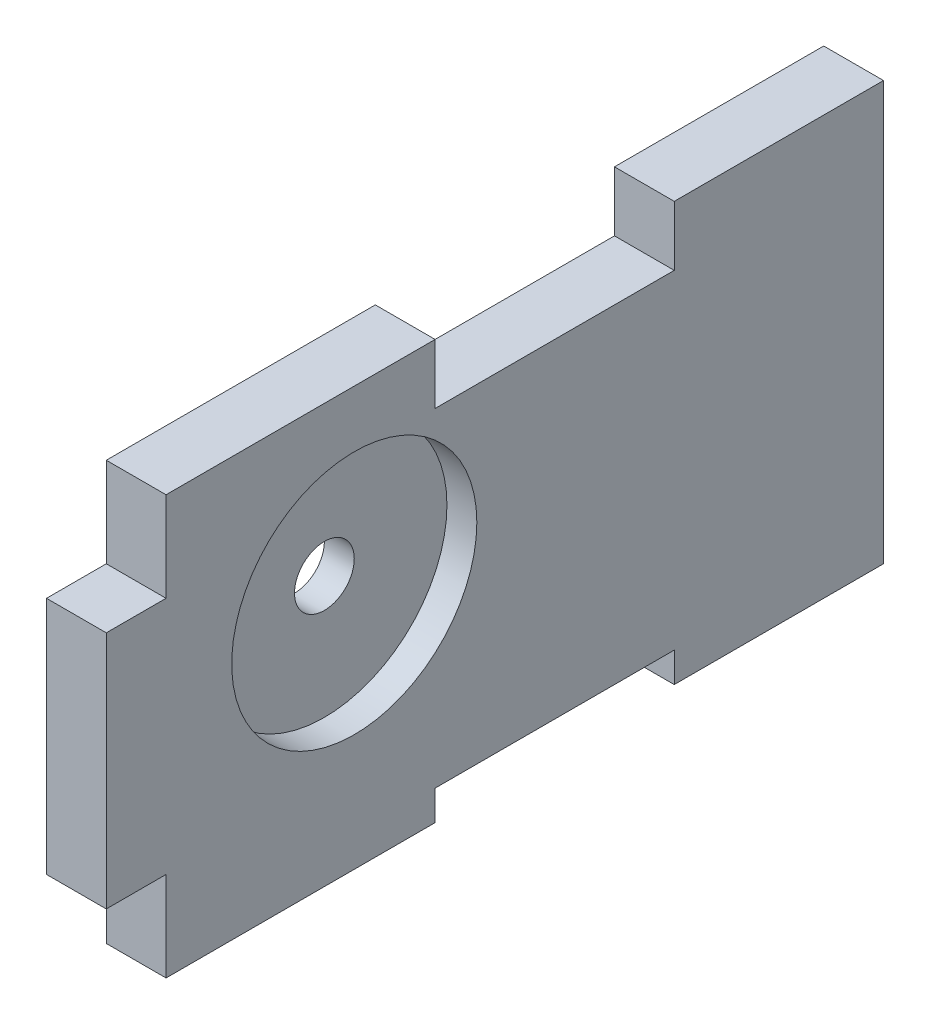
SolidWorks part; units mm, degrees
ref_plane "Front Plane" through (0, 0, 0) normal (0, 0, 1) x (1, 0, 0)
ref_plane "Top Plane" through (0, 0, 0) normal (0, 1, 0) x (1, 0, 0)
ref_plane "Right Plane" through (0, 0, 0) normal (1, 0, 0) x (0, 0, -1)
sketch "Sketch1" plane through (0, 0, 0) normal (1, 0, 0) x (0, 0, -1)
  line L1 (-130, 70) -> (0, 70)
  line L2 (-130, 70) -> (-130, 0)
  line L3 (-130, 0) -> (0, 0)
  line L4 (0, 70) -> (0, 0)
  line L5 (-130, 70) -> (-120, 70)
  line L6 (-130, 70) -> (-130, 55)
  line L7 (-130, 55) -> (-120, 55)
  line L8 (-120, 70) -> (-120, 55)
  line L9 (-130, 0) -> (-120, 0)
  line L10 (-130, 0) -> (-130, 15)
  line L11 (-130, 15) -> (-120, 15)
  line L12 (-120, 0) -> (-120, 15)
  line L13 (0, 70) -> (-10, 70)
  line L14 (0, 70) -> (0, 55)
  line L17 (0, 0) -> (-10, 0)
  line L18 (0, 0) -> (0, 15)
  line L21 (-75, 70) -> (-35, 70)
  line L22 (-75, 70) -> (-75, 60)
  line L23 (-75, 60) -> (-35, 60)
  line L24 (-35, 70) -> (-35, 60)
  line L25 (-75, 0) -> (-35, 0)
  line L26 (-75, 0) -> (-75, 5)
  line L27 (-75, 5) -> (-35, 5)
  line L28 (-35, 0) -> (-35, 5)
  dimension "D1" = 130
  dimension "D2" = 70
  dimension "D3" = 10
  dimension "D4" = 15
  dimension "D5" = 10
  dimension "D6" = 15
  dimension "D11" = 10
  dimension "D12" = 40
  dimension "D13" = 55
  dimension "D14" = 55
  dimension "D15" = 40
  dimension "D16" = 5
extrude "Boss-Extrude1" add sketch "Sketch1" along normal blind 10
sketch "Sketch2" plane through (10, 0, 0) normal (1, 0, 0) x (0, 0, -1)
  line L1 (-130, 55) -> (-130, 15) construction
  line L2 (-75, 5) -> (-35, 5) construction
  circle A0 centre (-88.52, 40) radius 20.5
  dimension "D3" = 41
  dimension "D1" = 35
  dimension "D2" = 41.48
extrude "Cut-Extrude1" cut sketch "Sketch2" against normal blind 5 contours A0
sketch "Sketch4" plane through (5, 0, 0) normal (1, 0, 0) x (0, 0, -1)
  circle A0 centre (-88.52, 40) radius 5
  dimension "D1" = 10
extrude "Cut-Extrude3" cut sketch "Sketch4" against normal through all
sketch "Sketch5" plane through (0, 0, 0) normal (-1, 0, 0) x (0, 0, 1)
  line L0 (75, 5) -> (35, 5) construction
  line L3 (120, 70) -> (120, 55) construction
  line L4 (0, 70) -> (0, 0) construction
  circle A0 centre (52.52, 33) radius 5
  circle A1 centre (17.11, 26.5091) radius 5
  dimension "D1" = 10
  dimension "D4" = 10
  dimension "D6" = 17.11
  dimension "D2" = 28
  dimension "D3" = 67.48
  dimension "D5" = 36
extrude "Cut-Extrude4" cut sketch "Sketch5" against normal blind 5 contours A1 | A0
sketch "Sketch6" plane through (0, 0, 0) normal (-1, 0, 0) x (0, 0, 1)
  line L1 (0, 15) -> (10, 15)
  line L2 (0, 15) -> (0, 55)
  line L3 (0, 55) -> (10, 55)
  line L4 (10, 15) -> (10, 55)
  line L5 (0, 70) -> (0, 0) construction
  point P4 (0, 35)
  point P7 (0, 35)
  point P9 (0, 56.7386)
  dimension "D1" = 10
  dimension "D2" = 40
extrude "Cut-Extrude5" cut sketch "Sketch6" against normal blind 5
